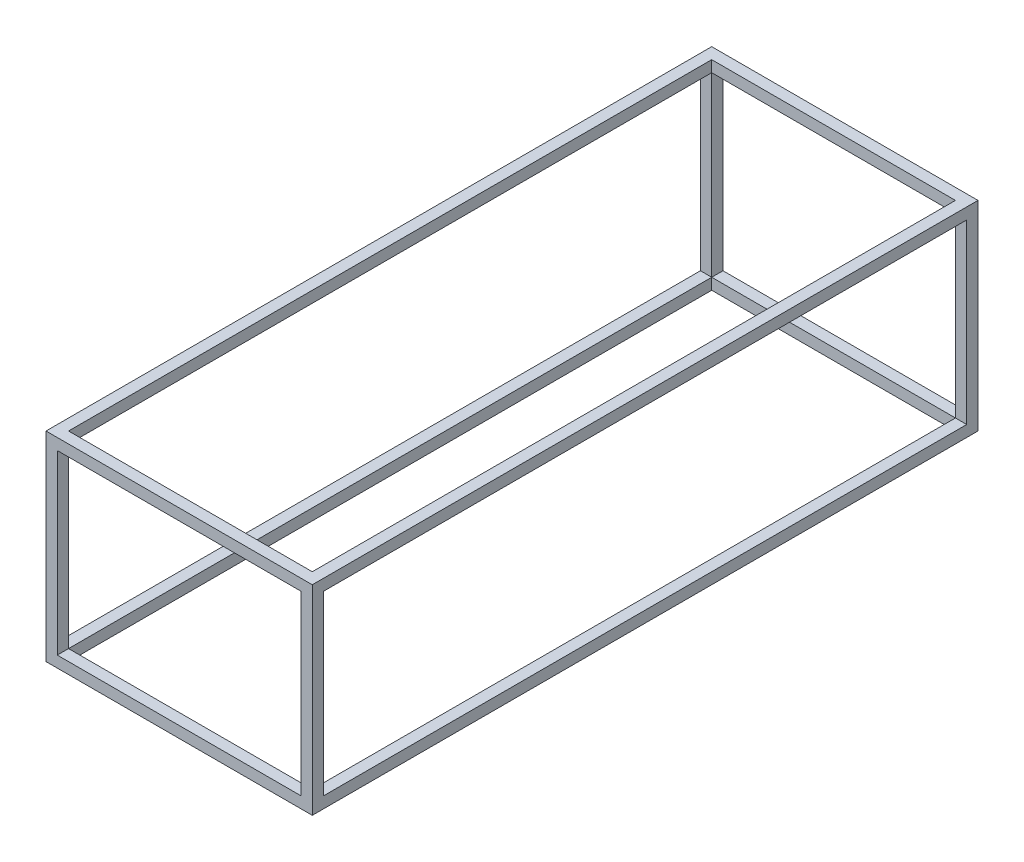
SolidWorks part; units mm, degrees
ref_plane "Front Plane" through (0, 0, 0) normal (0, 0, 1) x (1, 0, 0)
ref_plane "Top Plane" through (0, 0, 0) normal (0, 1, 0) x (1, 0, 0)
ref_plane "Right Plane" through (0, 0, 0) normal (1, 0, 0) x (0, 0, -1)
sketch "Sketch1" plane through (0, 0, 0) normal (0, 0, 1) x (1, 0, 0)
  line L0 (25.4, 424.6) -> (574.6, 424.6)
  line L1 (0, 0) -> (600, 0)
  line L2 (0, 0) -> (0, 450)
  line L3 (0, 450) -> (600, 450)
  line L4 (600, 0) -> (600, 450)
  line L5 (574.6, 25.4) -> (574.6, 424.6)
  line L6 (25.4, 25.4) -> (574.6, 25.4)
  line L7 (25.4, 25.4) -> (25.4, 424.6)
  dimension "D1" = 600
  dimension "D2" = 450
  dimension "D3" = 25.4
extrude "Boss-Extrude1" add sketch "Sketch1" along normal blind 25.4
sketch "Sketch2" plane through (0, 0, 0) normal (0, 0, -1) x (-1, 0, 0)
  line L1 (-25.4, 424.6) -> (0, 424.6)
  line L2 (-25.4, 424.6) -> (-25.4, 450)
  line L3 (-25.4, 450) -> (0, 450)
  line L4 (0, 424.6) -> (0, 450)
  line L5 (-574.6, 424.6) -> (-600, 424.6)
  line L6 (-574.6, 424.6) -> (-574.6, 450)
  line L7 (-574.6, 450) -> (-600, 450)
  line L8 (-600, 424.6) -> (-600, 450)
  line L9 (-574.6, 25.4) -> (-600, 25.4)
  line L10 (-574.6, 25.4) -> (-574.6, 0)
  line L11 (-574.6, 0) -> (-600, 0)
  line L12 (-600, 25.4) -> (-600, 0)
  line L13 (0, 0) -> (-25.4, 0)
  line L14 (0, 0) -> (0, 25.4)
  line L15 (0, 25.4) -> (-25.4, 25.4)
  line L16 (-25.4, 0) -> (-25.4, 25.4)
extrude "Boss-Extrude2" add sketch "Sketch2" against normal blind 1500
sketch "Sketch3" plane through (0, 0, 1500) normal (0, 0, 1) x (1, 0, 0)
  line L1 (25.4, 424.6) -> (574.6, 424.6)
  line L2 (25.4, 424.6) -> (25.4, 25.4)
  line L3 (25.4, 25.4) -> (574.6, 25.4)
  line L4 (600, 0) -> (600, 450)
  line L5 (0, 0) -> (600, 0)
  line L6 (0, 450) -> (0, 0)
  line L7 (600, 450) -> (0, 450)
  line L8 (600, 0) -> (600, 450)
  line L9 (0, 0) -> (600, 0)
  line L10 (0, 450) -> (0, 0)
  line L11 (600, 450) -> (0, 450)
  line L12 (574.6, 424.6) -> (574.6, 25.4)
  dimension "D1" = 0
extrude "Boss-Extrude3" add sketch "Sketch3" against normal blind 25.4
